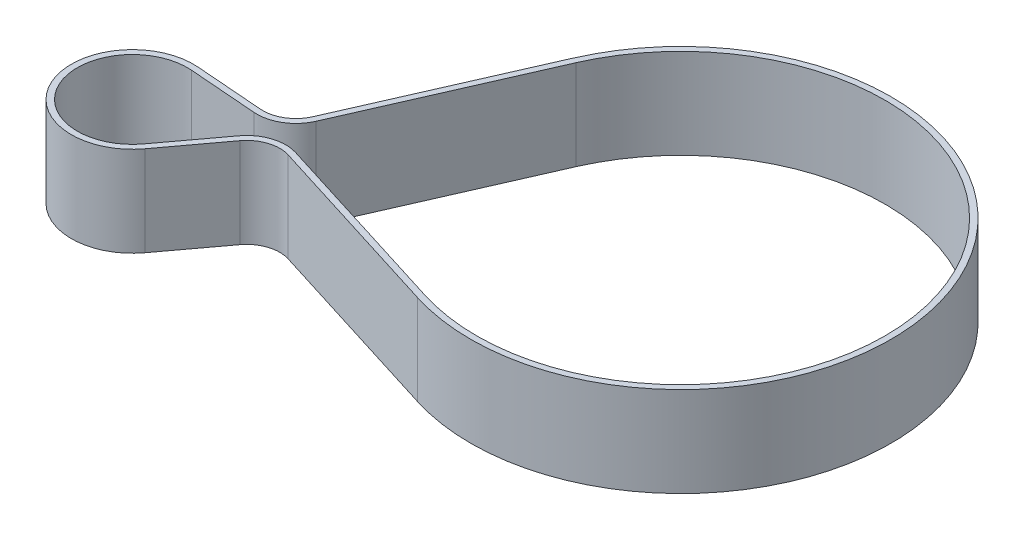
SolidWorks part; units mm, degrees
ref_plane "Front Plane" through (0, 0, 0) normal (0, 0, 1) x (1, 0, 0)
ref_plane "Top Plane" through (0, 0, 0) normal (0, 1, 0) x (1, 0, 0)
ref_plane "Right Plane" through (0, 0, 0) normal (1, 0, 0) x (0, 0, -1)
sketch "Sketch1" plane through (0, 0, 0) normal (0, 1, 0) x (1, 0, 0)
  line L0 (-42.6771, -21.763) -> (-31.4101, -22.6396)
  line L1 (-42.7547, -22.7599) -> (-31.4877, -23.6366)
  line L2 (-36.1046, -37.3702) -> (-29.366, -28.2979)
  line L3 (-35.3018, -37.9665) -> (-28.5632, -28.8942)
  line L4 (-25.9467, -19.3657) -> (-12.7445, 10.7302)
  line L5 (-25.031, -19.7674) -> (-11.8287, 10.3285)
  line L6 (-22.2077, -25.9701) -> (9.1583, -35.78)
  line L7 (-22.5062, -26.9245) -> (8.8598, -36.7344)
  circle A0 centre (19.3072, -3.33) radius 34
  circle A1 centre (19.3072, -3.33) radius 35
  circle A2 centre (-30.9834, -17.1562) radius 5.5
  circle A3 centre (-24.148, -32.1737) radius 5.5
  circle A4 centre (-24.148, -32.1737) radius 6.5
  circle A5 centre (-30.9834, -17.1562) radius 6.5
  circle A6 centre (-43.4661, -31.9023) radius 9.17
  circle A7 centre (-43.4661, -31.9023) radius 10.17
extrude "Boss-Extrude1" add sketch "Sketch1" along normal blind 15 contours A7 L2 A6 L1 | A7 L3 A4 L2 | A7 L1 A5 L0 | A5 L4 A2 L0 | L7 A4 L3 A3 | A5 L5 A1 L4 | A4 L7 A1 L6 | A1 L5 A0 L6
